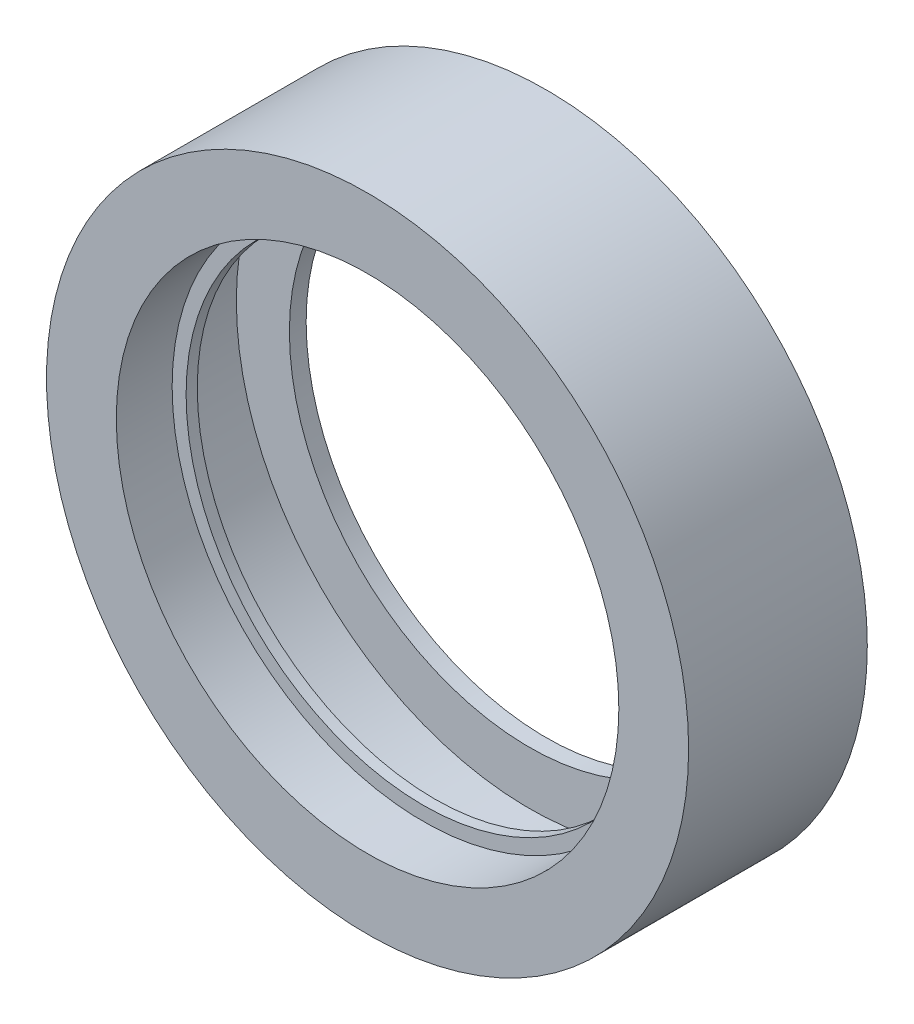
SolidWorks part; units mm, degrees
ref_plane "Front Plane" through (0, 0, 0) normal (0, 0, 1) x (1, 0, 0)
ref_plane "Top Plane" through (0, 0, 0) normal (0, 1, 0) x (1, 0, 0)
ref_plane "Right Plane" through (0, 0, 0) normal (1, 0, 0) x (0, 0, -1)
sketch "Sketch1" plane through (0, 0, 0) normal (0, 0, 1) x (1, 0, 0)
  circle A0 centre (0, 0) radius 52.5
  circle A1 centre (0, 0) radius 57.5
  dimension "D1" = 105
  dimension "D2" = 115
extrude "Boss-Extrude1" add sketch "Sketch1" along normal blind 32
ref_plane "Plane1" through (0, 0, 20) normal (0, 0, 1) x (1, 0, 0)
sketch "Sketch3" plane through (0, 0, 20) normal (0, 0, 1) x (1, 0, 0)
  circle A0 centre (0, 0) radius 35
  circle A1 centre (0, 0) radius 45
  circle A2 centre (0, 0) radius 52.5
  dimension "D1" = 90
  dimension "D2" = 70
  dimension "D3" = 105
extrude "Boss-Extrude3" add sketch "Sketch3" along normal up to surface (12 mm away) contours A2 A1 | A0 up to face at (57.5, 0, 32)
sketch "Sketch7" plane through (0, 0, 20) normal (0, 0, 1) x (1, 0, 0)
  circle A0 centre (0, 0) radius 42.5
  circle A1 centre (0, 0) radius 45
  dimension "D1" = 85
  dimension "D2" = 90
extrude "Boss-Extrude4" add sketch "Sketch7" along normal blind 2 contours A1 A0
sketch "Sketch10" plane through (0, 0, 0) normal (0, 0, -1) x (-1, 0, 0)
  circle A0 centre (0, 0) radius 43
  circle A1 centre (0, 0) radius 52.5
  dimension "D1" = 105
  dimension "D2" = 86
extrude "Boss-Extrude5" add sketch "Sketch10" against normal blind 3
ref_plane "Plane2" through (0, 0, 26) normal (0, 0, 1) x (1, 0, 0)
